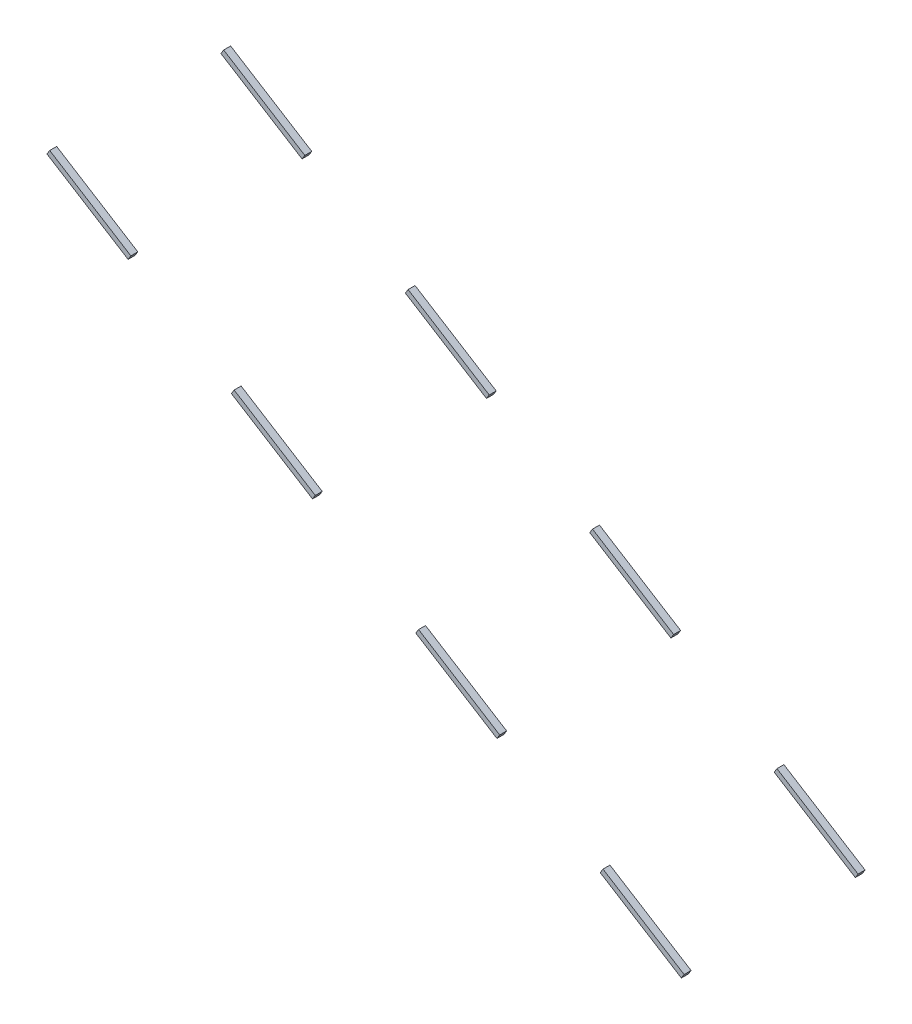
SolidWorks part; units mm, degrees
ref_plane "前视基准面" through (0, 0, 0) normal (0, 0, 1) x (1, 0, 0)
ref_plane "上视基准面" through (0, 0, 0) normal (0, 1, 0) x (1, 0, 0)
ref_plane "右视基准面" through (0, 0, 0) normal (1, 0, 0) x (0, 0, -1)
other "Configuration Table"
sketch "草图1" plane through (0, 0, 0) normal (0, 0, 1) x (1, 0, 0)
  line L0 (228.9704, 604.2027) -> (322.2557, 545.9116)
  line L1 (322.2557, 545.9116) -> (325.4352, 550.9999)
  line L2 (325.4352, 550.9999) -> (232.1499, 609.291)
  line L3 (232.1499, 609.291) -> (228.9704, 604.2027)
extrude "S1_110x8x6_SCHEMATIC" add sketch "草图1" along normal blind 8 from offset 146 separate body
sketch "草图2" plane through (0, 0, 0) normal (0, 0, 1) x (1, 0, 0)
  line L0 (440.9824, 471.7229) -> (534.2677, 413.4318)
  line L1 (534.2677, 413.4318) -> (537.4472, 418.52)
  line L2 (537.4472, 418.52) -> (444.1619, 476.8112)
  line L3 (444.1619, 476.8112) -> (440.9824, 471.7229)
extrude "S2_110x8x6_SCHEMATIC" add sketch "草图2" along normal blind 8 from offset 146 separate body
sketch "草图3" plane through (0, 0, 0) normal (0, 0, 1) x (1, 0, 0)
  line L0 (652.9944, 339.2431) -> (746.2797, 280.9519)
  line L1 (746.2797, 280.9519) -> (749.4592, 286.0402)
  line L2 (749.4592, 286.0402) -> (656.1739, 344.3314)
  line L3 (656.1739, 344.3314) -> (652.9944, 339.2431)
extrude "S3_110x8x6_SCHEMATIC" add sketch "草图3" along normal blind 8 from offset 146 separate body
sketch "草图4" plane through (0, 0, 0) normal (0, 0, 1) x (1, 0, 0)
  line L0 (865.0065, 206.7632) -> (958.2917, 148.4721)
  line L1 (958.2917, 148.4721) -> (961.4713, 153.5604)
  line L2 (961.4713, 153.5604) -> (868.186, 211.8515)
  line L3 (868.186, 211.8515) -> (865.0065, 206.7632)
extrude "S4_110x8x6_SCHEMATIC" add sketch "草图4" along normal blind 8 from offset 146 separate body
sketch "草图5" plane through (0, 0, 0) normal (0, 0, 1) x (1, 0, 0)
  line L0 (228.9704, 604.2027) -> (322.2557, 545.9116)
  line L1 (322.2557, 545.9116) -> (325.4352, 550.9999)
  line L2 (325.4352, 550.9999) -> (232.1499, 609.291)
  line L3 (232.1499, 609.291) -> (228.9704, 604.2027)
extrude "S5_110x8x6_SCHEMATIC" add sketch "草图5" along normal blind 8 from offset 346 separate body
sketch "草图6" plane through (0, 0, 0) normal (0, 0, 1) x (1, 0, 0)
  line L0 (440.9824, 471.7229) -> (534.2677, 413.4318)
  line L1 (534.2677, 413.4318) -> (537.4472, 418.52)
  line L2 (537.4472, 418.52) -> (444.1619, 476.8112)
  line L3 (444.1619, 476.8112) -> (440.9824, 471.7229)
extrude "S6_110x8x6_SCHEMATIC" add sketch "草图6" along normal blind 8 from offset 346 separate body
sketch "草图7" plane through (0, 0, 0) normal (0, 0, 1) x (1, 0, 0)
  line L0 (652.9944, 339.2431) -> (746.2797, 280.9519)
  line L1 (746.2797, 280.9519) -> (749.4592, 286.0402)
  line L2 (749.4592, 286.0402) -> (656.1739, 344.3314)
  line L3 (656.1739, 344.3314) -> (652.9944, 339.2431)
extrude "S7_110x8x6_SCHEMATIC" add sketch "草图7" along normal blind 8 from offset 346 separate body
sketch "草图8" plane through (0, 0, 0) normal (0, 0, 1) x (1, 0, 0)
  line L0 (865.0065, 206.7632) -> (958.2917, 148.4721)
  line L1 (958.2917, 148.4721) -> (961.4713, 153.5604)
  line L2 (961.4713, 153.5604) -> (868.186, 211.8515)
  line L3 (868.186, 211.8515) -> (865.0065, 206.7632)
extrude "S8_110x8x6_SCHEMATIC" add sketch "草图8" along normal blind 8 from offset 346 separate body
